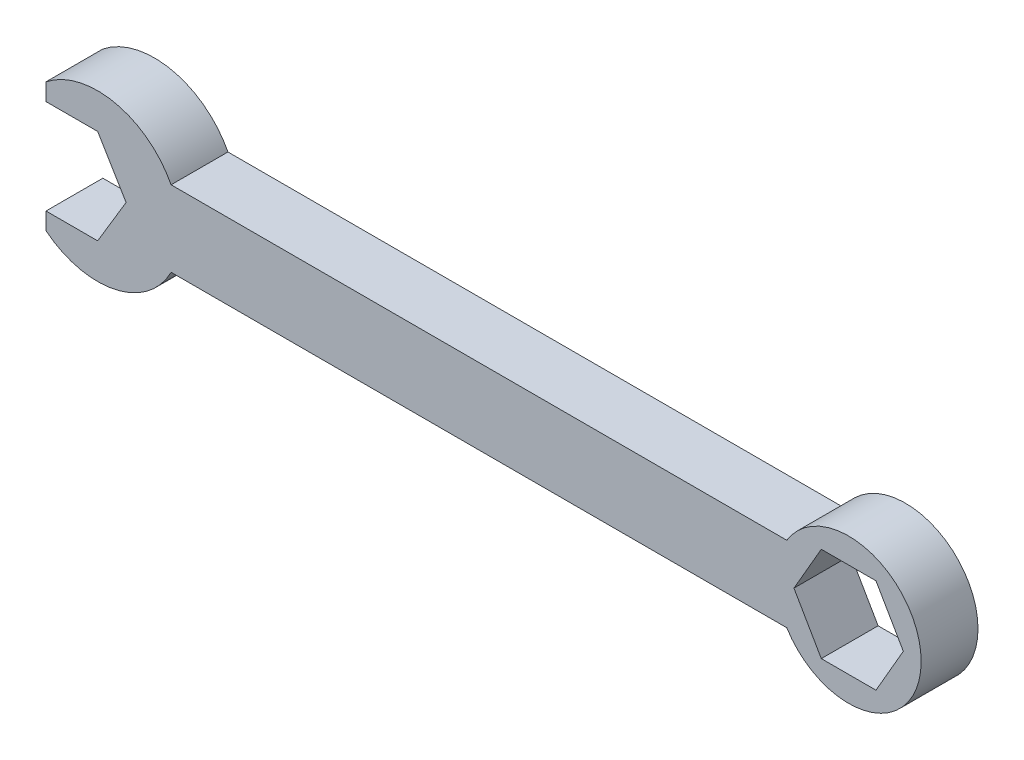
SolidWorks part; units mm, degrees
ref_plane "Front Plane" through (0, 0, 0) normal (0, 0, 1) x (1, 0, 0)
ref_plane "Top Plane" through (0, 0, 0) normal (0, 1, 0) x (1, 0, 0)
ref_plane "Right Plane" through (0, 0, 0) normal (1, 0, 0) x (0, 0, -1)
sketch "Sketch3" plane through (0, 0, 0) normal (0, 0, 1) x (1, 0, 0)
  line L1 (7.3323, 0) -> (3.6662, 6.35)
  line L2 (3.6662, 6.35) -> (-3.6662, 6.35)
  line L3 (-3.6662, 6.35) -> (-7.3323, 0)
  line L4 (-7.3323, 0) -> (-3.6662, -6.35)
  line L5 (-3.6662, -6.35) -> (3.6662, -6.35)
  line L6 (3.6662, -6.35) -> (7.3323, 0)
  line L7 (-100.6917, -6.35) -> (-96.8817, 0)
  line L8 (-90.8428, 5.08) -> (-8.2928, 5.08)
  line L9 (-90.8428, -5.08) -> (-8.2928, -5.08)
  line L10 (-107.6178, -8.6507) -> (-107.6178, -6.35)
  line L11 (-107.6178, -6.35) -> (-100.6917, -6.35)
  line L14 (-107.6178, 8.6507) -> (-107.6178, 6.35)
  line L15 (-107.6178, 6.35) -> (-100.6917, 6.35)
  line L16 (-100.6917, 6.35) -> (-96.8817, 0)
  circle A0 centre (0, 0) radius 9.7251
  circle A1 centre (0, 0) radius 6.35 construction
  arc A2 (-107.6178, -8.6507) -> (-107.6178, 8.6507) centre (-100.6917, 0) ccw
extrude "Boss-Extrude1" add sketch "Sketch3" along normal blind 7.62 contours A2 L14 L15 L16 L7 L11 L10 | A2 L9 A0 L8 | A0 L6 L5 L4 L3 L2 L1
